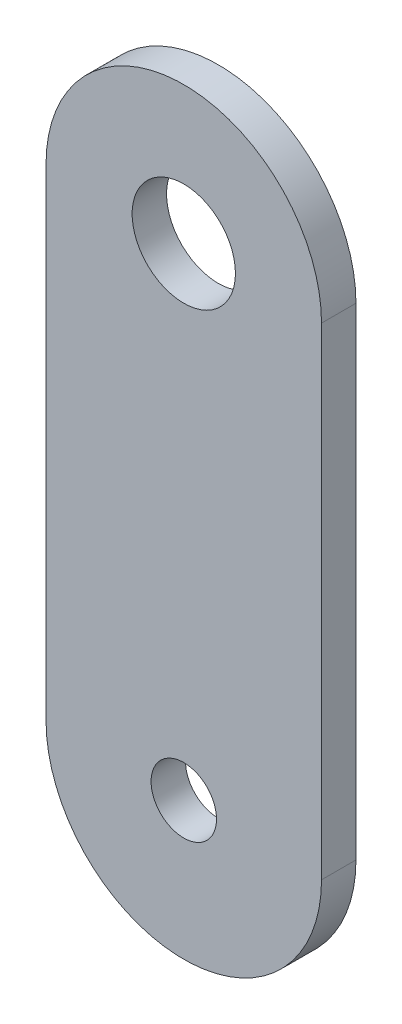
SolidWorks part; units mm, degrees
material "Plain Carbon Steel"
ref_plane "Front Plane" through (0, 0, 0) normal (0, 0, 1) x (1, 0, 0)
ref_plane "Top Plane" through (0, 0, 0) normal (0, 1, 0) x (1, 0, 0)
ref_plane "Right Plane" through (0, 0, 0) normal (1, 0, 0) x (0, 0, -1)
sketch "Sketch1" plane through (0, 0, 0) normal (0, 0, 1) x (1, 0, 0)
  line L0 (0, -70) -> (0, 70) construction
  line L7 (-40, -70) -> (-40, 70)
  line L8 (40, -70) -> (40, 70)
  arc A0 (-40, -70) -> (40, -70) centre (0, -70) ccw
  arc A1 (40, 70) -> (-40, 70) centre (0, 70) ccw
  point P0 (0, 0)
  point P8 (0, 0)
  dimension "D1" = 140
  dimension "D2" = 80
extrude "Boss-Extrude1" add sketch "Sketch1" along normal blind 10
sketch "Sketch2" plane through (0, 0, 10) normal (0, 0, 1) x (1, 0, 0)
  circle A0 centre (0, 70) radius 15
  circle A1 centre (0, -70) radius 9.5
  arc A2 (-40, -70) -> (40, -70) centre (0, -70) ccw construction
  arc A3 (40, 70) -> (-40, 70) centre (0, 70) ccw construction
  dimension "D1" = 30
  dimension "D3" = 19
extrude "Cut-Extrude1" cut sketch "Sketch2" against normal blind 10
